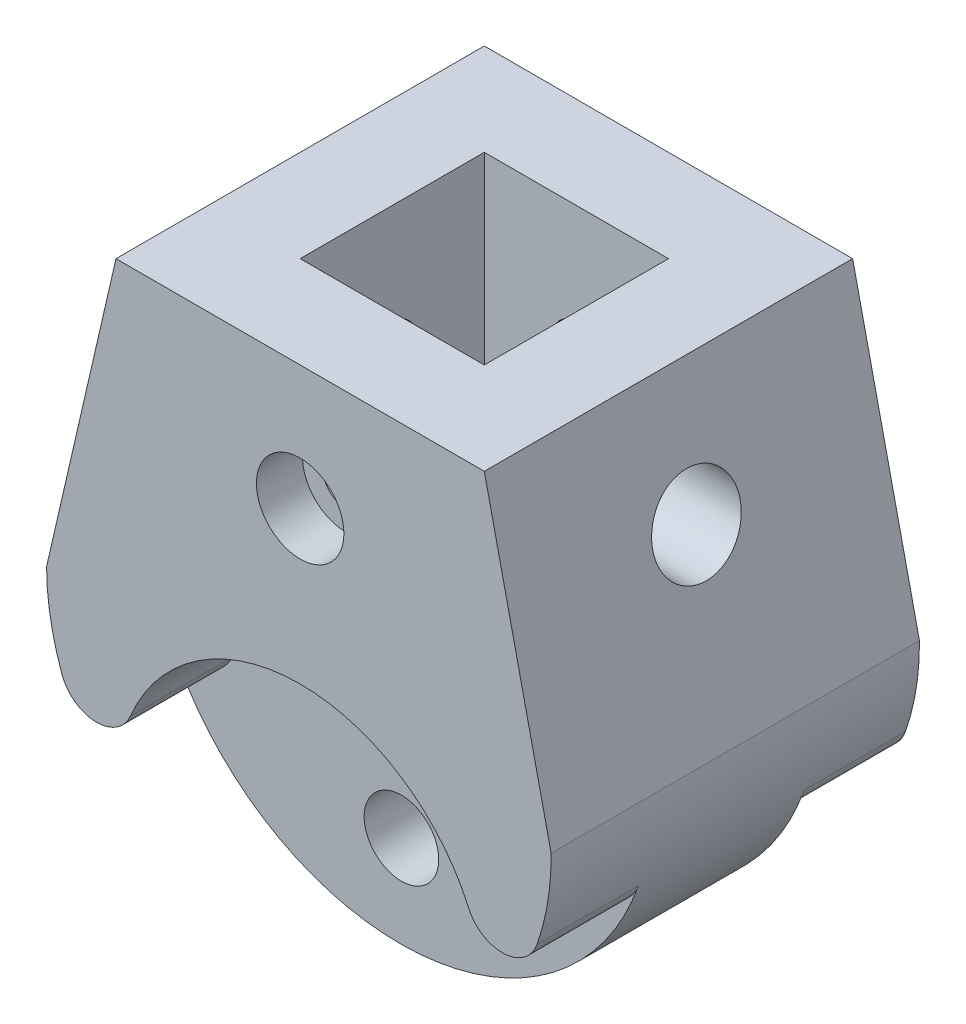
SolidWorks part; units mm, degrees
ref_plane "Alzado" through (0, 0, 0) normal (0, 0, 1) x (1, 0, 0)
ref_plane "Planta" through (0, 0, 0) normal (0, 1, 0) x (1, 0, 0)
ref_plane "Vista lateral" through (0, 0, 0) normal (1, 0, 0) x (0, 0, -1)
sketch "Croquis1" plane through (0, 0, 0) normal (0, 0, 1) x (1, 0, 0)
  line L0 (0, 0) -> (0, 50) construction
  line L1 (-20, 50) -> (20, 50)
  line L5 (-27.5407, 17.2557) -> (-20, 50)
  line L6 (27.2547, 17.704) -> (20, 50)
  line L7 (0, 0) -> (0, -32.5) construction
  line L8 (-20, -10) -> (20, -10) construction
  arc A3 (-27.5407, 17.2557) -> (0, -10) centre (-0.1425, 17.3982) ccw
  arc A4 (27.2547, 17.704) -> (0, -10) centre (-0.1425, 17.3986) cw
  circle A5 centre (0, 0) radius 4.05
  dimension "D1" = 27.3989
  dimension "D7" = 32.7443
  dimension "D8" = 32.296
  dimension "D9" = 27.3982
  dimension "D6" = 27.3986
  dimension "D11" = 8.1
  dimension "D2" = 50
  dimension "D3" = 40
  dimension "D4" = 20
  dimension "D5" = 10
  dimension "D10" = 12.969
extrude "Saliente-Extruir1" add sketch "Croquis1" along normal blind 40 contours A4 L6 L1 L5 A3 A5
sketch "Croquis2" plane through (0, 0, 40) normal (0, 0, 1) x (1, 0, 0)
  line L0 (0, 50) -> (0, -10) construction
  line L1 (-20, 50) -> (20, 50) construction
  circle A0 centre (0, 0) radius 4.05
  dimension "D1" = 8.1
extrude "Cortar-Extruir1" cut sketch "Croquis2" against normal blind 40
sketch "Croquis3" plane through (0, 0, 40) normal (0, 0, 1) x (1, 0, 0)
  line L0 (-20, 50) -> (20, 50) construction
  line L1 (0, -32.5) -> (0, 50) construction
  circle A5 centre (0, 0) radius 20
  dimension "D1" = 40
extrude "Cortar-Extruir10" cut sketch "Croquis3" against normal blind 11
sketch "Croquis4" plane through (0, 0, 0) normal (0, 0, -1) x (-1, 0, 0)
  circle A0 centre (0, 0) radius 20
  dimension "D1" = 40
extrude "Cortar-Extruir11" cut sketch "Croquis4" against normal blind 11
sketch "Croquis5" plane through (0, 50, 0) normal (0, 1, 0) x (1, 0, 0)
  line L0 (0, 0) -> (0, -40) construction
  line L1 (-20, -40) -> (20, -40) construction
  line L2 (-20, -20) -> (20, -20) construction
  line L3 (-20, -40) -> (-20, 0) construction
  line L4 (20, -40) -> (20, 0) construction
  line L6 (-10, -10) -> (10, -10)
  line L7 (-10, -10) -> (-10, -30)
  line L8 (-10, -30) -> (10, -30)
  line L9 (10, -10) -> (10, -30)
  line L10 (-10, -10) -> (10, -30) construction
  line L11 (-10, -30) -> (10, -10) construction
  point P11 (0, -20)
  dimension "D1" = 20
  dimension "D2" = 20
extrude "Cortar-Extruir12" cut sketch "Croquis5" against normal blind 27
sketch "Croquis6" plane through (0, 0, 40) normal (0, 0, 1) x (1, 0, 0)
  line L0 (0, 50) -> (0, -10) construction
  line L1 (-20, 50) -> (20, 50) construction
  line L2 (-10, 36.5) -> (10, 36.5) construction
  line L3 (-10, 23) -> (-10, 50) construction
  line L4 (10, 23) -> (10, 50) construction
  circle A0 centre (0, 36.5) radius 2.55
  dimension "D1" = 5.1
extrude "Cortar-Extruir13" cut sketch "Croquis6" against normal blind 47
sketch "Croquis7" plane through (0, 0, 40) normal (0, 0, 1) x (1, 0, 0)
  circle A0 centre (0, 36.5) radius 4.75
  dimension "D1" = 9.5
extrude "Cortar-Extruir14" cut sketch "Croquis7" against normal blind 5
sketch "Croquis8" plane through (0, 0, 0) normal (0, 0, -1) x (-1, 0, 0)
  circle A0 centre (0, 36.5) radius 4.75
  dimension "D1" = 9.5
extrude "Cortar-Extruir15" cut sketch "Croquis8" against normal blind 5
ref_plane "Plano5" through (27.2547, 0, 0) normal (1, 0, 0) x (0, 0, -1)
sketch "Croquis10" plane through (27.2547, 0, 0) normal (1, 0, 0) x (0, 0, -1)
  line L0 (-30, 36.5) -> (-10, 36.5) construction
  line L1 (-10, 23) -> (-10, 50) construction
  line L2 (-20, 50) -> (-20, 23) construction
  line L3 (-40, 50) -> (0, 50) construction
  line L4 (-30, 23) -> (-10, 23) construction
  line L5 (-30, 23) -> (-30, 50) construction
  circle A0 centre (-20, 36.5) radius 2.55
  dimension "D1" = 5.1
extrude "Cortar-Extruir16" cut sketch "Croquis10" against normal blind 61
sketch "Croquis11" plane through (27.2547, 0, 0) normal (1, 0, 0) x (0, 0, -1)
  circle A0 centre (-20, 36.5) radius 4.75
  dimension "D1" = 9.5
extrude "Cortar-Extruir17" cut sketch "Croquis11" against normal blind 12
ref_plane "Plano7" through (-27.5407, 0, 0) normal (-1, 0, 0) x (0, 0, 1)
sketch "Croquis12" plane through (-27.5407, 0, 0) normal (-1, 0, 0) x (0, 0, 1)
  circle A0 centre (20, 36.5) radius 4.75
  dimension "D1" = 9.5
extrude "Cortar-Extruir18" cut sketch "Croquis12" against normal blind 12
fillet "Redondeo2" radius 4 4 edges at (19.9631, -1.2151, 34.5) (-19.9405, -1.5418, 34.5) (-19.9405, -1.5418, 5.5) (19.9631, -1.2151, 5.5)
